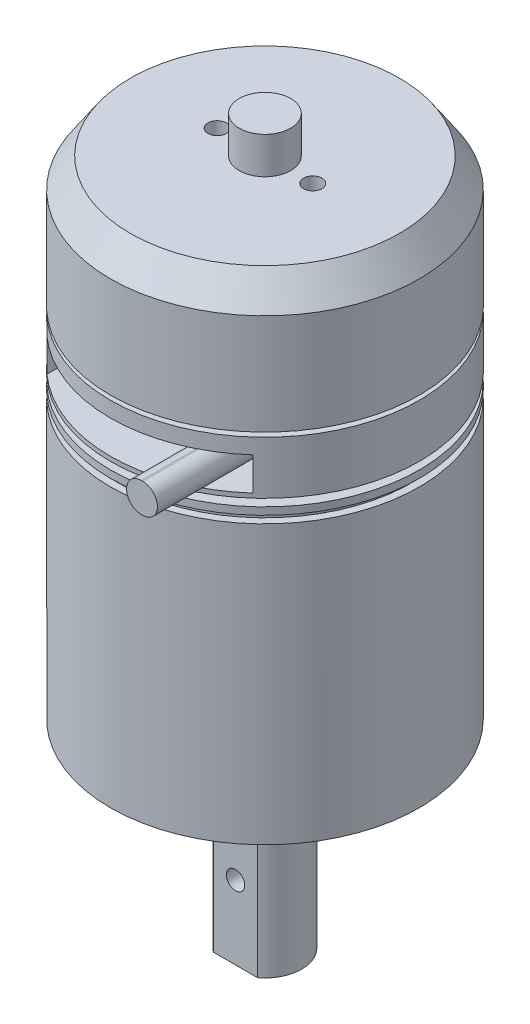
SolidWorks part; units mm, degrees
ref_plane "前视基准面" through (0, 0, 0) normal (0, 0, 1) x (1, 0, 0)
ref_plane "上视基准面" through (0, 0, 0) normal (0, 1, 0) x (1, 0, 0)
ref_plane "右视基准面" through (0, 0, 0) normal (1, 0, 0) x (0, 0, -1)
sketch "草图1" plane through (0, 0, 0) normal (0, 0, 1) x (1, 0, 0)
  line L0 (0, 0) -> (4.1, 0)
  line L1 (4.1, 0) -> (4.1, 6.7)
  line L2 (4.1, 6.7) -> (13.4, 6.7)
  line L3 (13.4, 6.7) -> (13.4, 8.7)
  line L4 (13.4, 8.7) -> (21, 8.7)
  line L5 (21, 8.7) -> (21, 10.2)
  line L6 (21, 10.2) -> (20, 10.2)
  line L7 (20, 10.2) -> (20, 11.2)
  line L8 (20, 11.2) -> (21, 11.2)
  line L9 (21, 11.2) -> (21, 12.2)
  line L10 (21, 12.2) -> (10, 12.2)
  line L11 (10, 12.2) -> (10, 13.2)
  line L12 (10, 13.2) -> (21, 13.2)
  line L13 (21, 13.2) -> (21, 20.4)
  line L14 (21, 20.4) -> (5, 20.4)
  line L15 (5, 20.4) -> (5, 21)
  line L16 (5, 21) -> (21, 21)
  line L17 (21, 21) -> (21, 34.7)
  line L18 (21, 34.7) -> (18.3, 38.7)
  line L19 (18.3, 38.7) -> (3.5, 38.7)
  line L20 (3.5, 38.7) -> (3.5, 43.7)
  line L21 (3.5, 43.7) -> (0, 43.7)
  line L22 (0, 43.7) -> (0, 0) construction
  line L23 (0, 0) -> (0, 43.7)
  dimension "D1" = 8.2
  dimension "D2" = 26.8
  dimension "D3" = 42
  dimension "D4" = 10
  dimension "D5" = 1.5
  dimension "D6" = 1
  dimension "D7" = 1
  dimension "D8" = 20
  dimension "D9" = 1
  dimension "D10" = 7.2
  dimension "D11" = 0.6
  dimension "D12" = 13.7
  dimension "D13" = 5
  dimension "D14" = 2
  dimension "D15" = 6.7
  dimension "D16" = 1
  dimension "D17" = 7
  dimension "D18" = 36.6
  dimension "D19" = 4
  dimension "D20" = 30
revolve "旋转1" add sketch "草图1" angle 360 about L22
ref_plane "基准面1" through (0, 0, 21) normal (0, 0, 1) x (1, 0, 0)
sketch "草图2" plane through (0, 0, 21) normal (0, 0, 1) x (1, 0, 0)
  line L1 (-14, 18.3) -> (14, 18.3)
  line L2 (-14, 18.3) -> (-14, 13.8)
  line L3 (-14, 13.8) -> (14, 13.8)
  line L4 (14, 18.3) -> (14, 13.8)
  line L5 (-14, 18.3) -> (14, 13.8) construction
  line L6 (-14, 13.8) -> (14, 18.3) construction
  line L7 (-21, 13.2) -> (21, 13.2) construction
  point P0 (0, 16.05)
  dimension "D1" = 28
  dimension "D2" = 4.5
  dimension "D3" = 0.6
extrude "切除-拉伸1" cut sketch "草图2" against normal blind 10
sketch "草图3" plane through (0, 0, 11) normal (0, 0, 1) x (1, 0, 0)
  line L0 (9.1851, 16.0532) -> (9.3851, 16.0532) construction
  line L1 (9.1851, 18.0532) -> (9.3851, 18.0532)
  line L2 (9.1851, 14.0532) -> (9.3851, 14.0532)
  arc A0 (9.1851, 18.0532) -> (9.1851, 14.0532) centre (9.1851, 16.0532) ccw
  arc A1 (9.3851, 14.0532) -> (9.3851, 18.0532) centre (9.3851, 16.0532) ccw
  point P2 (9.2851, 16.0532)
  dimension "D1" = 4
  dimension "D2" = 0.2
extrude "凸台-拉伸1" add sketch "草图3" along normal blind 15
hole_wizard "M3 螺纹孔1" positions "草图5" profile "草图6" tap size "M3" standard "GB"
sketch "草图5" plane through (0, 38.7, 0) normal (0, 1, 0) x (1, 0, 0)
  line L0 (0, 0) -> (0, 8.0606) construction
  point P0 (-6.5, 0)
  point P2 (6.5, 0)
  dimension "D1" = 13
sketch "草图6" plane through (-6.5, 38.7, 0) normal (1, 0, 0) x (0, 0, 1)
  line L0 (0, 0) -> (0, 4.7511)
  line L1 (0, 4.7511) -> (1.25, 4)
  line L2 (1.25, 4) -> (1.25, 0)
  line L5 (1.25, 0) -> (0, 0)
  line L10 (0, 4.7511) -> (-1.25, 4) construction
  line L11 (0, -6.35) -> (0, 107.95) construction
  dimension "螺纹孔钻头直径" = 2.5
  dimension "螺纹孔钻头深度" = 4
  dimension "导头角度" = 118
cosmetic thread "孔螺蚊线1" parameters "D1"=4, "D2"=3
cosmetic thread "孔螺蚊线2" parameters "D1"=4, "D2"=3
sketch "草图7" plane through (0, 0, 0) normal (0, 0, 1) x (1, 0, 0)
  line L0 (0, 8.7) -> (0, -54.6) construction
  line L1 (-13.4, 8.7) -> (13.4, 8.7) construction
  line L2 (0, -54.6) -> (5, -54.6)
  line L3 (5, -54.6) -> (5, -30.5)
  line L4 (5, -30.5) -> (8.275, -30.5)
  line L5 (13, -29.6) -> (13, -27.6)
  line L6 (13, -27.6) -> (21, -27.6)
  line L7 (21, -27.6) -> (21, 8.7)
  line L8 (-21, 8.7) -> (21, 8.7) construction
  line L9 (21, 8.7) -> (0, 8.7)
  line L10 (18.3, 38.7) -> (-18.3, 38.7) construction
  line L11 (13, -29.6) -> (8.275, -29.6)
  line L12 (8.275, -29.6) -> (8.275, -30.5)
  line L13 (0, 8.7) -> (0, -54.6)
  dimension "D1" = 66.3
  dimension "D2" = 2
  dimension "D3" = 0.9
  dimension "D4" = 27
  dimension "D5" = 26
  dimension "D6" = 10
  dimension "D7" = 16.55
revolve "旋转2" add sketch "草图7" angle 360 about L0
sketch "草图8" plane through (0, -54.6, 0) normal (0, -1, 0) x (1, 0, 0)
  line L0 (-3, 4) -> (3, 4)
  circle A0 centre (0, 0) radius 5 construction
  circle A1 centre (0, 0) radius 5 construction
  arc A2 (3, 4) -> (-3, 4) centre (0, 0) ccw
  dimension "D1" = 4
extrude "切除-拉伸2" cut sketch "草图8" against normal blind 20
hole_wizard "M4 螺纹孔1" positions "草图10" profile "草图9" tap size "M4" standard "GB"
sketch "草图10" plane through (0, -27.6, 0) normal (0, -1, 0) x (-1, 0, 0)
  circle A0 centre (0, 0) radius 17.5
  point P5 (0, -17.5)
  point P7 (-17.5, 0)
  point P9 (0, 17.5)
  point P11 (17.5, 0)
  dimension "D1" = 35
sketch "草图9" plane through (-17.5, -27.6, 0) normal (1, 0, 0) x (0, 0, -1)
  line L0 (0, 0) -> (0, 11.0914)
  line L1 (0, 11.0914) -> (1.65, 10.1)
  line L2 (1.65, 10.1) -> (1.65, 0)
  line L5 (1.65, 0) -> (0, 0)
  line L10 (0, 11.0914) -> (-1.65, 10.1) construction
  line L11 (0, -6.35) -> (0, 107.95) construction
  dimension "螺纹孔钻头直径" = 3.3
  dimension "螺纹孔钻头深度" = 10.1
  dimension "导头角度" = 118
cosmetic thread "孔螺蚊线3" parameters "D1"=8, "D2"=4
cosmetic thread "孔螺蚊线4" parameters "D1"=8, "D2"=4
cosmetic thread "孔螺蚊线5" parameters "D1"=8, "D2"=4
cosmetic thread "孔螺蚊线6" parameters "D1"=8, "D2"=4
sketch "草图11" plane through (0, 0, 4) normal (0, 0, 1) x (1, 0, 0)
  line L0 (0, -54.6) -> (0, -36.079) construction
  line L1 (-3, -54.6) -> (3, -54.6) construction
  line L2 (-13.929, -44.6) -> (10.5915, -44.6) construction
  circle A0 centre (0, -44.6) radius 1.9071
  dimension "D1" = 10
hole_wizard "M3 螺纹孔2" positions "3D草图1" profile "草图12" tap size "M3" standard "GB" end condition through all
sketch3d "3D草图1"
  point P0 (0, -44.6, 4)
sketch "草图12" plane through (0, -44.6, 4) normal (1, 0, 0) x (0, -1, 0)
  line L0 (0, 0) -> (0, 25)
  line L1 (0, 25) -> (1.25, 25)
  line L2 (1.25, 25) -> (1.25, 0)
  line L5 (1.25, 0) -> (0, 0)
  line L11 (0, -6.35) -> (0, 107.95) construction
  dimension "螺纹线主直径" = 2.5
  dimension "通孔螺纹孔钻头深度" = 25
sketch "草图15" plane through (0, -54.6, 0) normal (0, -1, 0) x (1, 0, 0)
  point P0 (0, 0)
hole_wizard "M5 螺纹孔1" positions "3D草图5" profile "草图16" tap size "M5" standard "GB"
sketch3d "3D草图5"
  point P0 (0, -54.6, 0)
  point P3 (0, -54.6, 0)
sketch "草图16" plane through (0, -54.6, 0) normal (1, 0, 0) x (0, 0, -1)
  line L0 (0, 0) -> (0, 15.2618)
  line L1 (0, 15.2618) -> (2.1, 14)
  line L2 (2.1, 14) -> (2.1, 0)
  line L5 (2.1, 0) -> (0, 0)
  line L10 (0, 15.2618) -> (-2.1, 14) construction
  line L11 (0, -6.35) -> (0, 107.95) construction
  dimension "螺纹孔钻头直径" = 4.2
  dimension "螺纹孔钻头深度" = 14
  dimension "导头角度" = 118
cosmetic thread "孔螺蚊线8" parameters "D1"=10, "D2"=5
